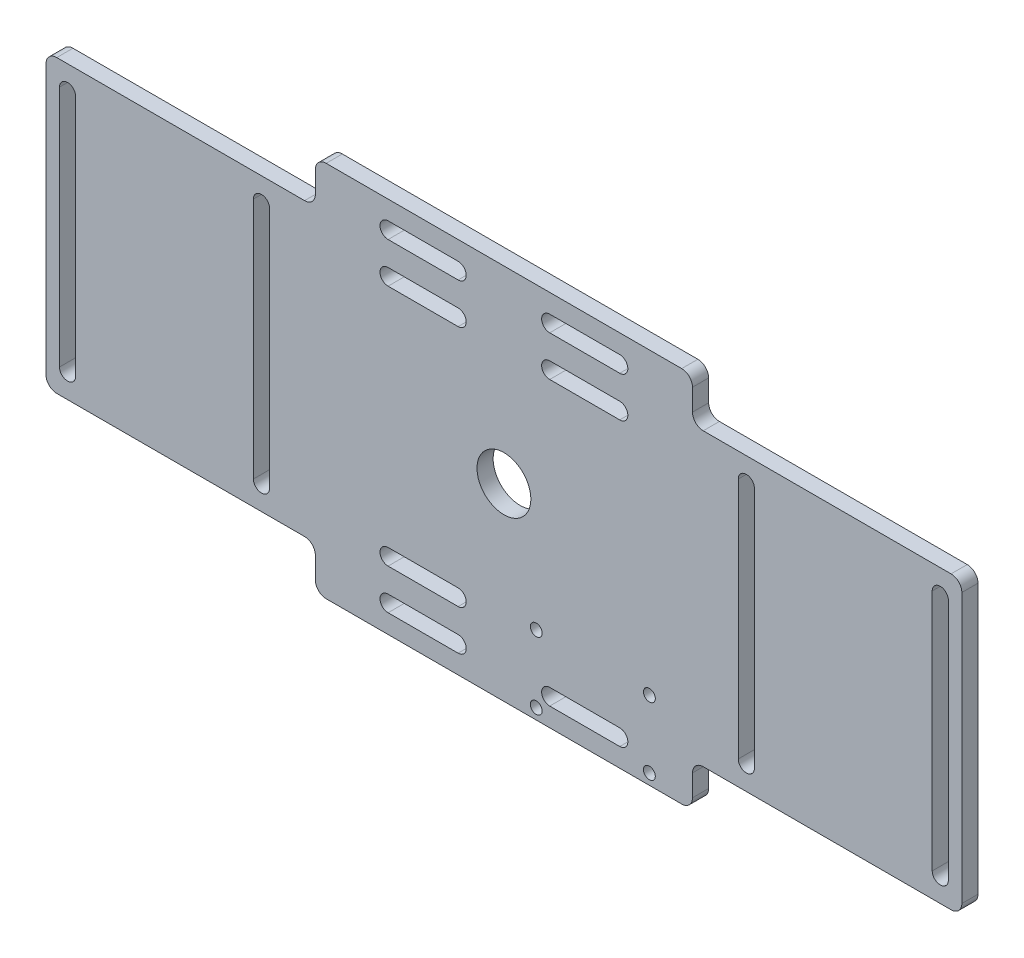
SolidWorks part; units mm, degrees
ref_plane "前基準面" through (0, 0, 0) normal (0, 0, 1) x (1, 0, 0)
ref_plane "上基準面" through (0, 0, 0) normal (0, 1, 0) x (1, 0, 0)
ref_plane "右基準面" through (0, 0, 0) normal (1, 0, 0) x (0, 0, -1)
sketch "草圖1" plane through (0, 0, 0) normal (0, 0, 1) x (1, 0, 0)
  line L1 (-85, 35) -> (85, 35)
  line L2 (-85, 35) -> (-85, -35)
  line L3 (-85, -35) -> (85, -35)
  line L4 (85, 35) -> (85, -35)
  line L5 (-85, 35) -> (85, -35) construction
  line L6 (-85, -35) -> (85, 35) construction
  point P0 (0, 0)
  dimension "D1" = 170
  dimension "D2" = 70
extrude "填料-伸長1" add sketch "草圖1" along normal blind 3
sketch "草圖2" plane through (0, 0, 3) normal (0, 0, 1) x (1, 0, 0)
  line L0 (-1000, 0) -> (49000, 0) construction
  line L1 (45, -986.1952) -> (45, 49013.8048) construction
  line L2 (-81, -962.7943) -> (-81, 49037.2057) construction
  line L3 (45, -22.5) -> (45, 22.5) construction
  line L4 (43.5, -22.5) -> (43.5, 22.5)
  line L5 (46.5, -22.5) -> (46.5, 22.5)
  line L6 (-45, -1000) -> (-45, 49000) construction
  line L7 (-45, -22.5) -> (-45, 22.5) construction
  line L8 (-46.5, -22.5) -> (-46.5, 22.5)
  line L9 (-43.5, -22.5) -> (-43.5, 22.5)
  line L10 (0, -1000) -> (0, 49000) construction
  line L11 (-1010.5287, 30) -> (48989.4713, 30) construction
  line L12 (-1007.193, -30) -> (48992.807, -30) construction
  line L13 (21.5, -30) -> (8.5, -30) construction
  line L16 (6, -996.0597) -> (6, 49003.9403) construction
  line L19 (81, -968.4295) -> (81, 49031.5705) construction
  line L20 (-81, -22.5) -> (-81, 22.5) construction
  line L21 (-82.5, -22.5) -> (-82.5, 22.5)
  line L22 (-79.5, -22.5) -> (-79.5, 22.5)
  line L23 (81, -22.5) -> (81, 22.5) construction
  line L24 (79.5, -22.5) -> (79.5, 22.5)
  line L25 (82.5, -22.5) -> (82.5, 22.5)
  line L26 (27, -997.4467) -> (27, 49002.5533) construction
  line L27 (-1014.4971, -33) -> (48985.5029, -33) construction
  line L28 (-1015.8254, -20.5) -> (48984.1746, -20.5) construction
  line L29 (-85, -35) -> (85, -35) construction
  line L30 (21.5, -31.5) -> (8.5, -31.5)
  line L33 (21.5, -28.5) -> (8.5, -28.5)
  line L34 (-21.5, -30) -> (-8.5, -30) construction
  line L35 (-21.5, -31.5) -> (-8.5, -31.5)
  line L36 (-21.5, -28.5) -> (-8.5, -28.5)
  line L37 (21.5, 30) -> (8.5, 30) construction
  line L38 (21.5, 31.5) -> (8.5, 31.5)
  line L39 (21.5, 28.5) -> (8.5, 28.5)
  line L40 (-21.5, 30) -> (-8.5, 30) construction
  line L41 (-21.5, 31.5) -> (-8.5, 31.5)
  line L42 (-21.5, 28.5) -> (-8.5, 28.5)
  line L43 (21.5, 22.5) -> (8.5, 22.5) construction
  line L44 (21.5, 24) -> (8.5, 24)
  line L45 (21.5, 21) -> (8.5, 21)
  line L46 (-21.5, 22.5) -> (-8.5, 22.5) construction
  line L47 (-21.5, 24) -> (-8.5, 24)
  line L48 (-21.5, 21) -> (-8.5, 21)
  line L49 (-21.5, -22.5) -> (-8.5, -22.5) construction
  line L50 (-21.5, -24) -> (-8.5, -24)
  line L51 (-21.5, -21) -> (-8.5, -21)
  arc A0 (43.5, -22.5) -> (46.5, -22.5) centre (45, -22.5) ccw
  arc A1 (46.5, 22.5) -> (43.5, 22.5) centre (45, 22.5) ccw
  arc A2 (-46.5, -22.5) -> (-43.5, -22.5) centre (-45, -22.5) ccw
  arc A3 (-43.5, 22.5) -> (-46.5, 22.5) centre (-45, 22.5) ccw
  arc A12 (-82.5, -22.5) -> (-79.5, -22.5) centre (-81, -22.5) ccw
  arc A13 (-79.5, 22.5) -> (-82.5, 22.5) centre (-81, 22.5) ccw
  arc A14 (79.5, -22.5) -> (82.5, -22.5) centre (81, -22.5) ccw
  arc A15 (82.5, 22.5) -> (79.5, 22.5) centre (81, 22.5) ccw
  circle A16 centre (0, 0) radius 5
  circle A17 centre (27, -20.5) radius 1.1
  circle A18 centre (6, -20.5) radius 1.1
  circle A19 centre (6, -33) radius 1.1
  circle A20 centre (27, -33) radius 1.1
  arc A23 (21.5, -31.5) -> (21.5, -28.5) centre (21.5, -30) ccw
  arc A24 (8.5, -28.5) -> (8.5, -31.5) centre (8.5, -30) ccw
  arc A25 (-21.5, -31.5) -> (-21.5, -28.5) centre (-21.5, -30) cw
  arc A26 (-8.5, -28.5) -> (-8.5, -31.5) centre (-8.5, -30) cw
  arc A27 (21.5, 31.5) -> (21.5, 28.5) centre (21.5, 30) cw
  arc A28 (8.5, 28.5) -> (8.5, 31.5) centre (8.5, 30) cw
  arc A29 (-21.5, 31.5) -> (-21.5, 28.5) centre (-21.5, 30) ccw
  arc A30 (-8.5, 28.5) -> (-8.5, 31.5) centre (-8.5, 30) ccw
  arc A31 (21.5, 24) -> (21.5, 21) centre (21.5, 22.5) cw
  arc A32 (8.5, 21) -> (8.5, 24) centre (8.5, 22.5) cw
  arc A33 (-21.5, 24) -> (-21.5, 21) centre (-21.5, 22.5) ccw
  arc A34 (-8.5, 21) -> (-8.5, 24) centre (-8.5, 22.5) ccw
  arc A35 (-21.5, -24) -> (-21.5, -21) centre (-21.5, -22.5) cw
  arc A36 (-8.5, -21) -> (-8.5, -24) centre (-8.5, -22.5) cw
  point P9 (45, 0)
  point P16 (-45, 0)
  point P31 (15, -30)
  point P47 (-81, 0)
  point P54 (81, 0)
  point P72 (-15, -30)
  point P81 (15, 30)
  point P88 (-15, 30)
  point P97 (15, 22.5)
  point P102 (-15, 22.5)
  point P110 (-15, -22.5)
  dimension "D10" = 1.5
  dimension "D20" = 10
  dimension "D21" = 2.2
  dimension "D2" = 45
  dimension "D3" = 3
  dimension "D4" = 90
  dimension "D5" = 45
  dimension "D6" = 3
  dimension "D7" = 45
  dimension "D8" = 60
  dimension "D9" = 30
  dimension "D11" = 13
  dimension "D12" = 12.5
  dimension "D13" = 21
  dimension "D14" = 162
  dimension "D15" = 81
  dimension "D16" = 3
  dimension "D17" = 45
  dimension "D18" = 45
  dimension "D19" = 3
  dimension "D22" = 2
  dimension "D23" = 6
  dimension "D24" = 8.5
  dimension "D25" = 2
  dimension "D26" = 2
extrude "除料-伸長1" cut sketch "草圖2" against normal through all
sketch "草圖4" plane through (0, 0, 3) normal (0, 0, 1) x (1, 0, 0)
  line L0 (85, -35) -> (85, 35) construction
  line L1 (85, 35) -> (35, 35)
  line L2 (85, 35) -> (85, 27)
  line L3 (83, 27) -> (37, 27)
  line L4 (35, 33) -> (35, 29)
  line L5 (85, 35) -> (-85, 35) construction
  line L6 (-103.8053, 0) -> (147.3737, 0) construction
  line L7 (33, 35) -> (35, 35)
  line L8 (85, 27) -> (85, 25)
  line L9 (0, 92.8328) -> (0, -104.1404) construction
  line L10 (85, -27) -> (85, -25)
  line L11 (33, -35) -> (35, -35)
  line L12 (35, -33) -> (35, -29)
  line L13 (83, -27) -> (37, -27)
  line L14 (85, -35) -> (85, -27)
  line L15 (85, -35) -> (35, -35)
  line L16 (-85, -35) -> (-35, -35)
  line L17 (-85, -35) -> (-85, -27)
  line L18 (-83, -27) -> (-37, -27)
  line L19 (-35, -33) -> (-35, -29)
  line L20 (-33, -35) -> (-35, -35)
  line L21 (-85, -27) -> (-85, -25)
  line L22 (-85, 27) -> (-85, 25)
  line L23 (-33, 35) -> (-35, 35)
  line L24 (-35, 33) -> (-35, 29)
  line L25 (-83, 27) -> (-37, 27)
  line L26 (-85, 35) -> (-85, 27)
  line L27 (-85, 35) -> (-35, 35)
  arc A0 (85, 25) -> (83, 27) centre (83, 25) ccw
  arc A1 (37, 27) -> (35, 29) centre (37, 29) cw
  arc A2 (35, 33) -> (33, 35) centre (33, 33) ccw
  arc A3 (35, -33) -> (33, -35) centre (33, -33) cw
  arc A4 (37, -27) -> (35, -29) centre (37, -29) ccw
  arc A5 (85, -25) -> (83, -27) centre (83, -25) cw
  arc A6 (-85, -25) -> (-83, -27) centre (-83, -25) ccw
  arc A7 (-37, -27) -> (-35, -29) centre (-37, -29) cw
  arc A8 (-35, -33) -> (-33, -35) centre (-33, -33) ccw
  arc A9 (-35, 33) -> (-33, 35) centre (-33, 33) cw
  arc A10 (-37, 27) -> (-35, 29) centre (-37, 29) ccw
  arc A11 (-85, 25) -> (-83, 27) centre (-83, 25) cw
  dimension "D3" = 2
  dimension "D4" = 2
  dimension "D5" = 2
  dimension "D1" = 8
  dimension "D2" = 50
  dimension "D6" = 2
extrude "除料-伸長2" cut sketch "草圖4" against normal through all
